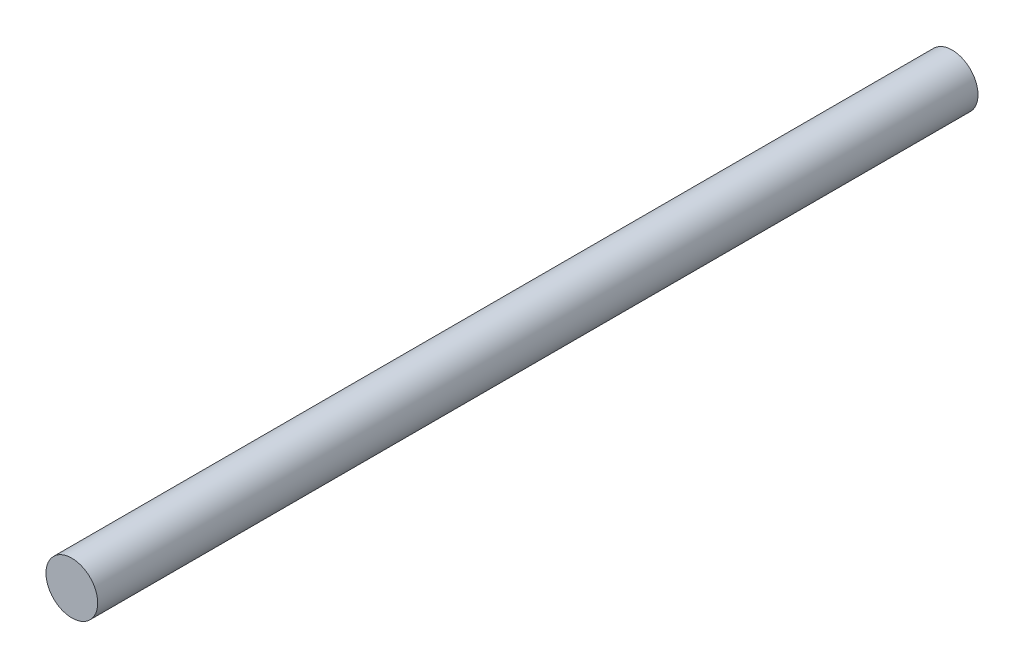
SolidWorks part; units mm, degrees
ref_plane "Plan de face" through (0, 0, 0) normal (0, 0, 1) x (1, 0, 0)
ref_plane "Plan de dessus" through (0, 0, 0) normal (0, 1, 0) x (1, 0, 0)
ref_plane "Plan de droite" through (0, 0, 0) normal (1, 0, 0) x (0, 0, -1)
sketch "Esquisse1" plane through (0, 0, 0) normal (0, 0, 1) x (1, 0, 0)
  circle A0 centre (0, 0) radius 10
  dimension "D1" = 20
extrude "Boss.-Extru.1" add sketch "Esquisse1" along normal blind 340
